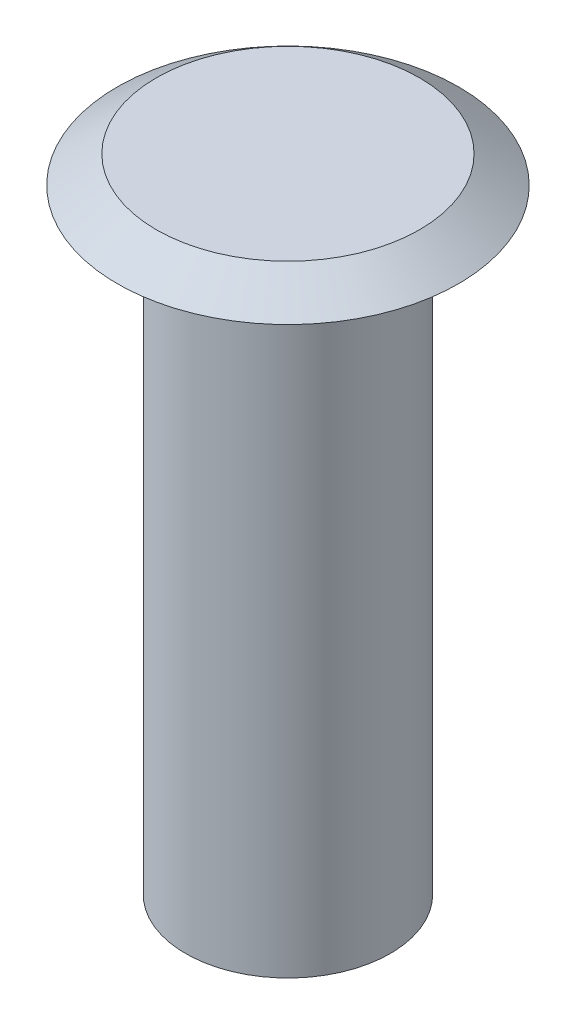
SolidWorks part; units mm, degrees
ref_plane "前视基准面" through (0, 0, 0) normal (0, 0, 1) x (1, 0, 0)
ref_plane "上视基准面" through (0, 0, 0) normal (0, 1, 0) x (1, 0, 0)
ref_plane "右视基准面" through (0, 0, 0) normal (1, 0, 0) x (0, 0, -1)
other "Configuration Table"
sketch "草图1" plane through (0, 0, 0) normal (0, 0, 1) x (1, 0, 0)
  line L0 (0, 0) -> (0, 9.4) construction
  line L1 (0, 9.4) -> (-1.9287, 9.4)
  line L2 (-1.9287, 9.4) -> (-2.5, 9)
  line L3 (-2.5, 9) -> (-1.5, 9)
  line L4 (-1.5, 9) -> (-1.5, 0)
  line L5 (-1.5, 0) -> (-0.6, 0)
  line L6 (-0.6, 0) -> (-0.6, 4)
  line L7 (-0.6, 4) -> (0, 4)
  line L8 (0, 4) -> (0, 9.4)
  dimension "D1" = 1.2
  dimension "D2" = 3
  dimension "D3" = 9
  dimension "D4" = 4
  dimension "D5" = 0.4
  dimension "D6" = 145
  dimension "D7" = 5
revolve "旋转1" add sketch "草图1" angle 360 about L0
